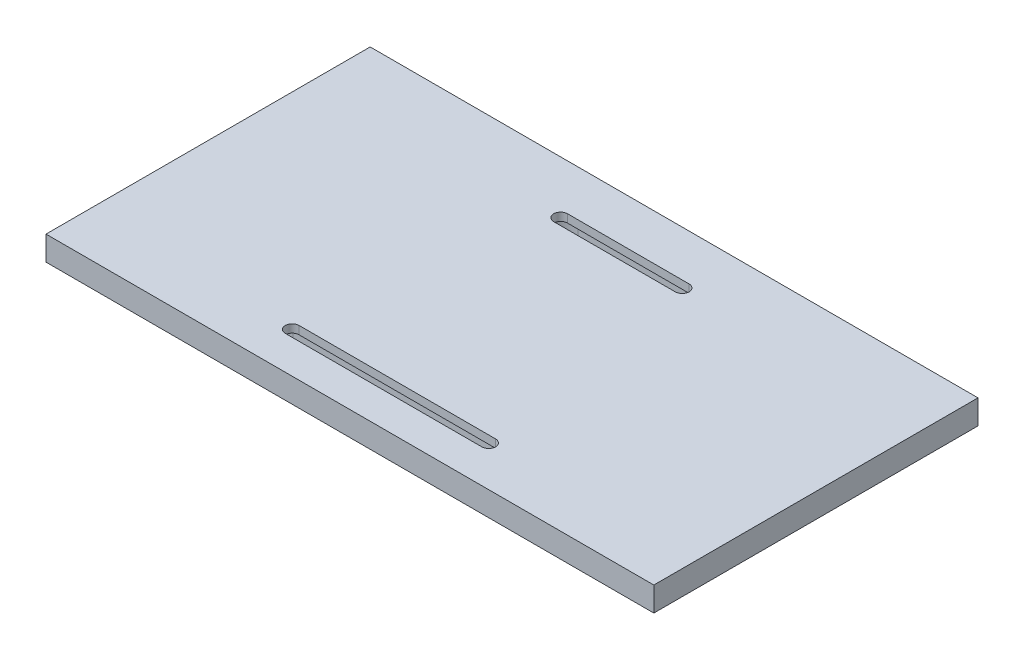
SolidWorks part; units mm, degrees
ref_plane "Front" through (0, 0, 0) normal (0, 0, 1) x (1, 0, 0)
ref_plane "Top" through (0, 0, 0) normal (0, 1, 0) x (1, 0, 0)
ref_plane "Right" through (0, 0, 0) normal (1, 0, 0) x (0, 0, -1)
sketch "Esquisse2" plane through (0, 0, 0) normal (0, 1, 0) x (1, 0, 0)
  line L1 (0, 0) -> (150, 0)
  line L2 (0, 0) -> (0, 80)
  line L3 (0, 80) -> (150, 80)
  line L4 (150, 0) -> (150, 80)
  dimension "D1" = 150
  dimension "D2" = 80
extrude "Boss.-Extru.1" add sketch "Esquisse2" along normal blind 6
hole_wizard "Chambrage pour vis à tête hexagonale M31" positions "Esquisse3D2" profile "Esquisse5" counterbore size "M3" standard "ISO"
sketch3d "Esquisse3D2"
  line L0 (150, 0, 0) -> (150, 0, -80) construction
  line L7 (0, 0, 0) -> (150, 0, 0) construction
  line L13 (50.75, 0, -10) -> (61.8742, 0, -10) construction
  line L15 (99.25, 0, -10) -> (89.6403, 0, -10) construction
  point P0 (90, 0, -67)
  point P2 (60, 0, -67)
  point P4 (50.75, 0, -10)
  point P6 (99.25, 0, -10)
  dimension "D1" = 30
  dimension "D2" = 48.5
  dimension "D3" = 60
  dimension "D4" = 50.75
  dimension "D5" = 57
  dimension "D6" = 10
  dimension "D7" = 57
  dimension "D8" = 10
sketch "Esquisse5" plane through (90, 0, -67) normal (1, 0, 0) x (0, 0, -1)
  line L0 (0, 0) -> (0, 16.0215)
  line L1 (0, 16.0215) -> (1.7, 15)
  line L2 (1.7, 15) -> (1.7, 3.4)
  line L3 (1.7, 3.4) -> (3.25, 3.4)
  line L4 (3.25, 3.4) -> (3.25, 0)
  line L5 (3.25, 0) -> (0, 0)
  line L10 (0, 16.0215) -> (-1.7, 15) construction
  line L11 (0, -6.35) -> (0, 107.95) construction
  dimension "Diamètre du perçage" = 3.4
  dimension "Profondeur du perçage" = 15
  dimension "Diamètre du chambrage" = 6.5
  dimension "Profondeur du chambrage" = 3.4
  dimension "Angle de pointe" = 118
sketch "Esquisse6" plane through (0, 0, 0) normal (0, -1, 0) x (1, 0, 0)
  line L0 (90, -67) -> (60, -67) construction
  line L3 (90, -71.2787) -> (60, -71.2787)
  line L4 (90, -62.7213) -> (60, -62.7213)
  arc A5 (90, -71.2787) -> (90, -62.7213) centre (90, -67) ccw
  arc A6 (60, -62.7213) -> (60, -71.2787) centre (60, -67) ccw
  point P3 (75, -67)
extrude "Enlèv. mat.-Extru.2" cut sketch "Esquisse6" against normal blind 4
sketch "Esquisse7" plane through (0, 0, 0) normal (0, -1, 0) x (1, 0, 0)
  line L0 (90, -67) -> (60, -67) construction
  line L1 (90, -68.7) -> (60, -68.7)
  line L2 (90, -65.3) -> (60, -65.3)
  arc A0 (90, -68.7) -> (90, -65.3) centre (90, -67) ccw
  arc A1 (60, -65.3) -> (60, -68.7) centre (60, -67) ccw
  point P4 (75, -67)
  dimension "D1" = 3.4
extrude "Enlèv. mat.-Extru.3" cut sketch "Esquisse7" against normal through all
sketch "Esquisse9" plane through (0, 0, 0) normal (0, -1, 0) x (-1, 0, 0)
  line L0 (-102.5, 10) -> (-47.5, 10) construction
  line L1 (-102.5, 13.5) -> (-47.5, 13.5)
  line L2 (-102.5, 6.5) -> (-47.5, 6.5)
  circle A0 centre (-99.25, 10) radius 3.25 construction
  circle A1 centre (-99.25, 10) radius 3.25 construction
  circle A2 centre (-50.75, 10) radius 3.25 construction
  arc A3 (-102.5, 13.5) -> (-102.5, 6.5) centre (-102.5, 10) ccw
  arc A4 (-47.5, 6.5) -> (-47.5, 13.5) centre (-47.5, 10) ccw
  point P9 (-75, 10)
  dimension "D1" = 7
extrude "Enlèv. mat.-Extru.4" cut sketch "Esquisse9" against normal blind 4
sketch "Esquisse10" plane through (0, 4, 0) normal (0, -1, 0) x (-1, 0, 0)
  line L0 (-99.25, 10) -> (-50.75, 10) construction
  line L1 (-99.25, 11.7) -> (-50.75, 11.7)
  line L2 (-99.25, 8.3) -> (-50.75, 8.3)
  arc A0 (-99.25, 11.7) -> (-99.25, 8.3) centre (-99.25, 10) ccw
  arc A1 (-50.75, 8.3) -> (-50.75, 11.7) centre (-50.75, 10) ccw
  point P4 (-75, 10)
  dimension "D1" = 3.4
extrude "Enlèv. mat.-Extru.5" cut sketch "Esquisse10" against normal blind 4
